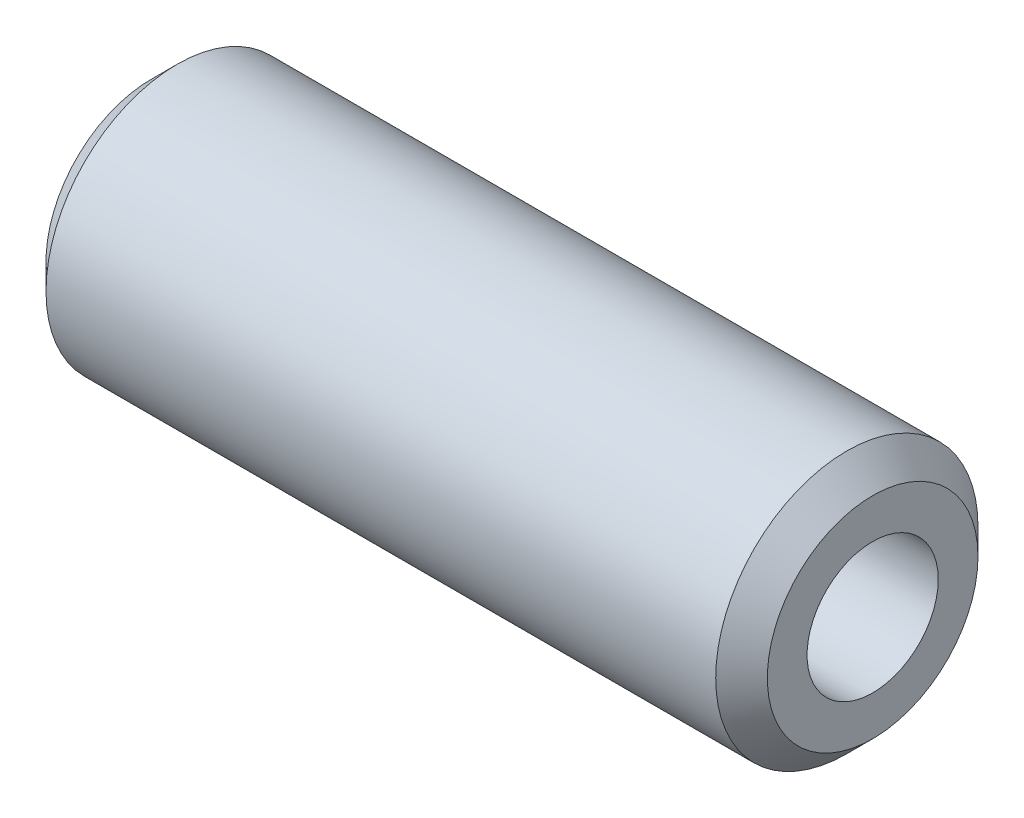
SolidWorks part; units mm, degrees
ref_plane "Front Plane" through (0, 0, 0) normal (0, 0, 1) x (1, 0, 0)
ref_plane "Top Plane" through (0, 0, 0) normal (0, 1, 0) x (1, 0, 0)
ref_plane "Right Plane" through (0, 0, 0) normal (1, 0, 0) x (0, 0, -1)
sketch "Sketch1" plane through (0, 0, 0) normal (1, 0, 0) x (0, 0, -1)
  circle A0 centre (0, 0) radius 12.7
  circle A1 centre (0, 0) radius 6.35
  dimension "D1" = 12.7
  dimension "D2" = 25.4
extrude "Boss-Extrude1" add sketch "Sketch1" along normal blind 69.85
chamfer "Chamfer1" distance 2.5 angle 45 2 edges at (69.85, 0, -12.7) (0, 0, -12.7)
